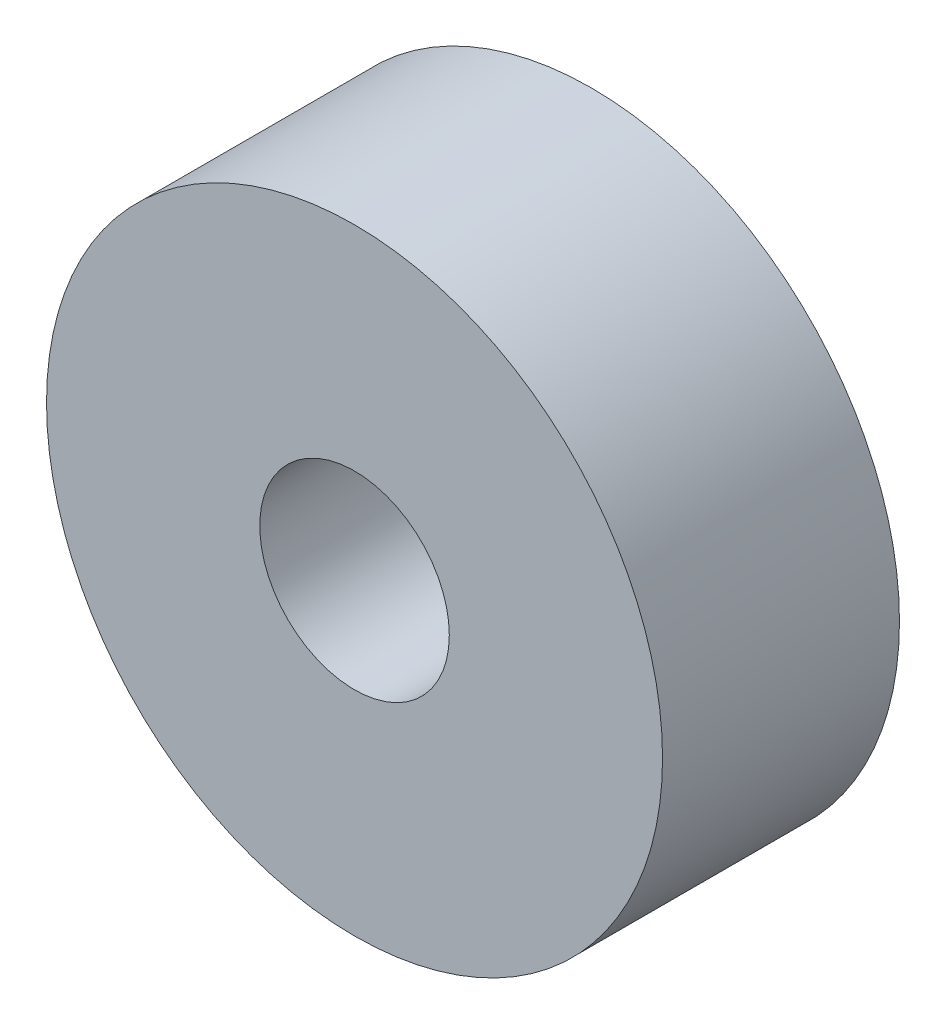
SolidWorks part; units mm, degrees
ref_plane "Front Plane" through (0, 0, 0) normal (0, 0, 1) x (1, 0, 0)
ref_plane "Top Plane" through (0, 0, 0) normal (0, 1, 0) x (1, 0, 0)
ref_plane "Right Plane" through (0, 0, 0) normal (1, 0, 0) x (0, 0, -1)
sketch "Sketch1" plane through (0, 0, 0) normal (0, 0, 1) x (1, 0, 0)
  circle A0 centre (0, 0) radius 6.5
  circle A1 centre (0, 0) radius 2
  dimension "D1" = 4
  dimension "D2" = 13
extrude "Boss-Extrude1" add sketch "Sketch1" along normal blind 5
